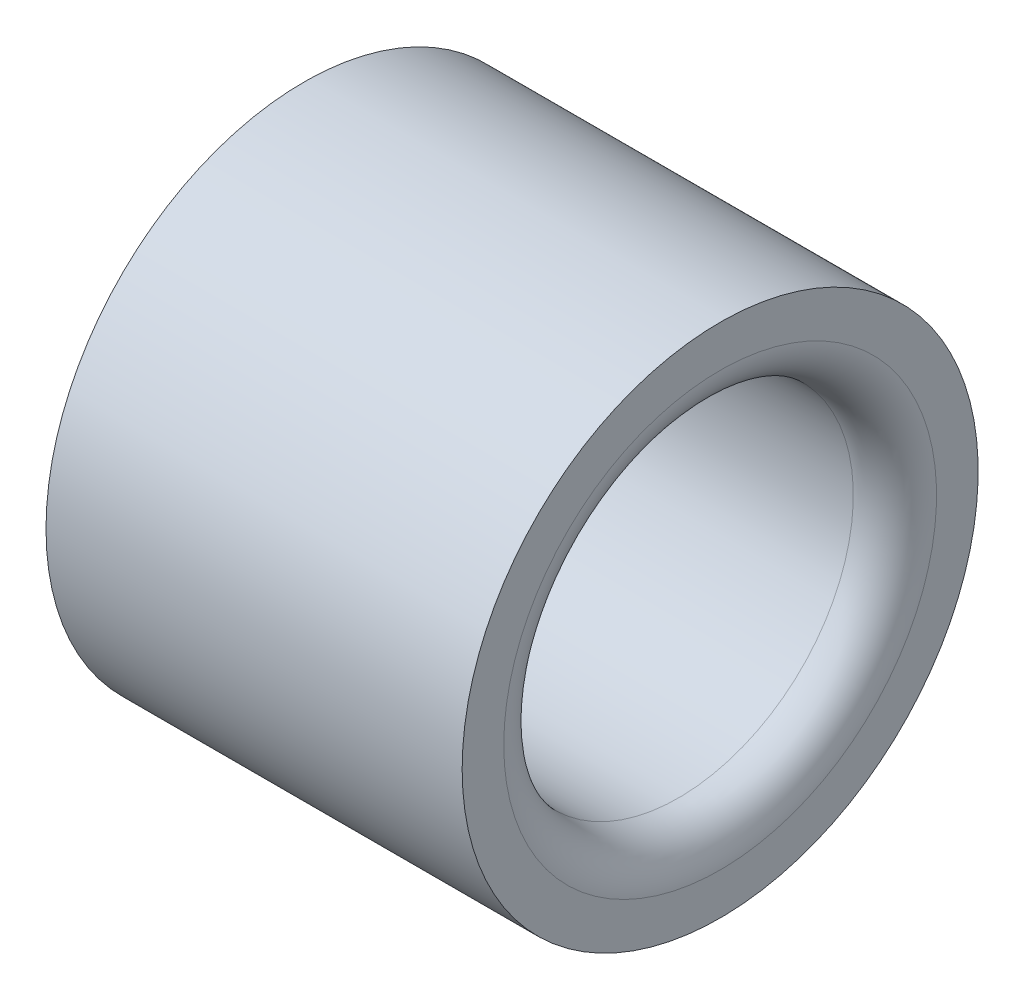
SolidWorks part; units mm, degrees
ref_plane "Front Plane" through (0, 0, 0) normal (0, 0, 1) x (1, 0, 0)
ref_plane "Top Plane" through (0, 0, 0) normal (0, 1, 0) x (1, 0, 0)
ref_plane "Right Plane" through (0, 0, 0) normal (1, 0, 0) x (0, 0, -1)
sketch "Sketch1" plane through (0, 0, 0) normal (0, 0, 1) x (1, 0, 0)
  line L0 (0, 2.7) -> (1.4236, 2.7)
  line L1 (1.4236, 2.7) -> (1.4236, 4.2)
  line L2 (1.4236, 4.2) -> (10, 4.2)
  line L3 (10, 4.2) -> (10, 6.2)
  line L4 (10, 6.2) -> (0, 6.2)
  line L5 (0, 6.2) -> (0, 2.7)
  line L6 (0, 0) -> (6.7708, 0) construction
  dimension "D1" = 5.4
  dimension "D2" = 8.4
  dimension "D3" = 10
  dimension "D4" = 2
revolve "Revolve1" add sketch "Sketch1" angle 360 about L6
fillet "Fillet1" radius 1 1 edges at (10, 0, 4.2)
